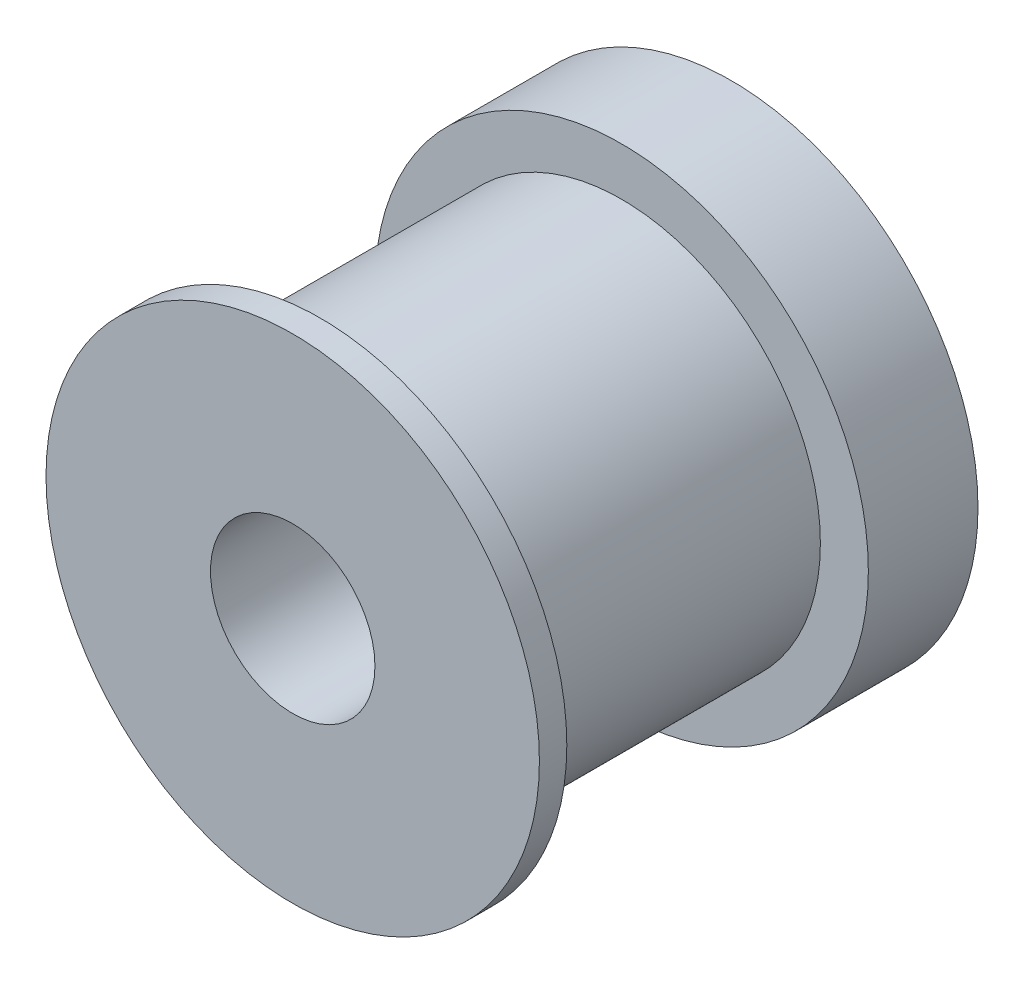
SolidWorks part; units mm, degrees
ref_plane "Front Plane" through (0, 0, 0) normal (0, 0, 1) x (1, 0, 0)
ref_plane "Top Plane" through (0, 0, 0) normal (0, 1, 0) x (1, 0, 0)
ref_plane "Right Plane" through (0, 0, 0) normal (1, 0, 0) x (0, 0, -1)
sketch "Sketch1" plane through (0, 0, 0) normal (0, 0, 1) x (1, 0, 0)
  circle A0 centre (0, 0) radius 3
  circle A1 centre (0, 0) radius 9
  dimension "D1" = 6
  dimension "D2" = 18
extrude "Boss-Extrude1" add sketch "Sketch1" along normal blind 4
sketch "Sketch2" plane through (0, 0, 4) normal (0, 0, 1) x (1, 0, 0)
  circle A0 centre (0, 0) radius 3
  circle A1 centre (0, 0) radius 7.25
  circle A2 centre (0, 0) radius 3 construction
  dimension "D1" = 14.5
extrude "Boss-Extrude2" add sketch "Sketch2" along normal blind 11
sketch "Sketch3" plane through (0, 0, 15) normal (0, 0, 1) x (1, 0, 0)
  circle A0 centre (0, 0) radius 3
  circle A1 centre (0, 0) radius 9
  circle A2 centre (0, 0) radius 3 construction
  dimension "D1" = 18
extrude "Boss-Extrude3" add sketch "Sketch3" along normal blind 1
scale "Echelle1" scale about centroid uniform scaling yes scale factor 2
scale "Echelle2" scale about centroid uniform scaling yes scale factor 0.25
